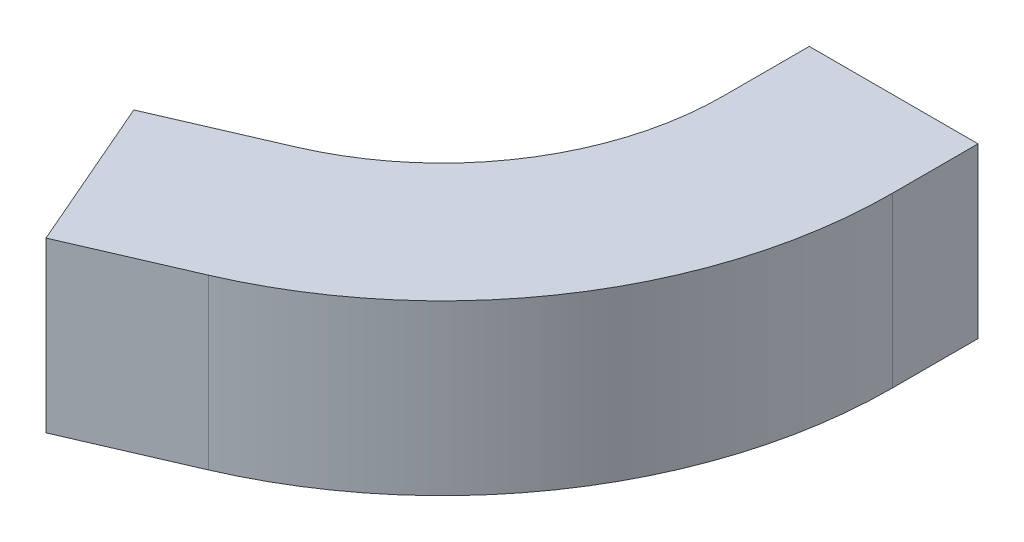
SolidWorks part; units mm, degrees
ref_plane "Front Plane" through (0, 0, 0) normal (0, 0, 1) x (1, 0, 0)
ref_plane "Top Plane" through (0, 0, 0) normal (0, 1, 0) x (1, 0, 0)
ref_plane "Right Plane" through (0, 0, 0) normal (1, 0, 0) x (0, 0, -1)
sketch "Sketch1" plane through (0, 0, 0) normal (0, 1, 0) x (1, 0, 0)
  line L0 (0, 0) -> (40, 0)
  line L1 (0, 0) -> (15.8923, -36.7074)
  line L2 (15.8923, -36.7074) -> (5.8253, -41.0659)
  line L3 (25, 0) -> (40, 0)
  line L4 (25, 0) -> (25, 7.62)
  line L5 (25, 7.62) -> (40, 7.62)
  line L6 (40, 0) -> (40, 7.62)
  line L7 (5.8253, -41.0659) -> (-0.1343, -27.3006)
  line L8 (-0.1343, -27.3006) -> (9.9327, -22.9421)
  circle A0 centre (0, 0) radius 40
  circle A1 centre (0, 0) radius 25
  dimension "D1" = 15
  dimension "D2" = 80
  dimension "D3" = 66.59
  dimension "D4" = 7.62
  dimension "D5" = 10.97
extrude "Boss-Extrude1" add sketch "Sketch1" along normal blind 15 contours L7 A0 L1 L8 | A1 L1 A0 L0 | L0 A0 L5 L4 | A0 L7 L2 | A0 L6 L5
